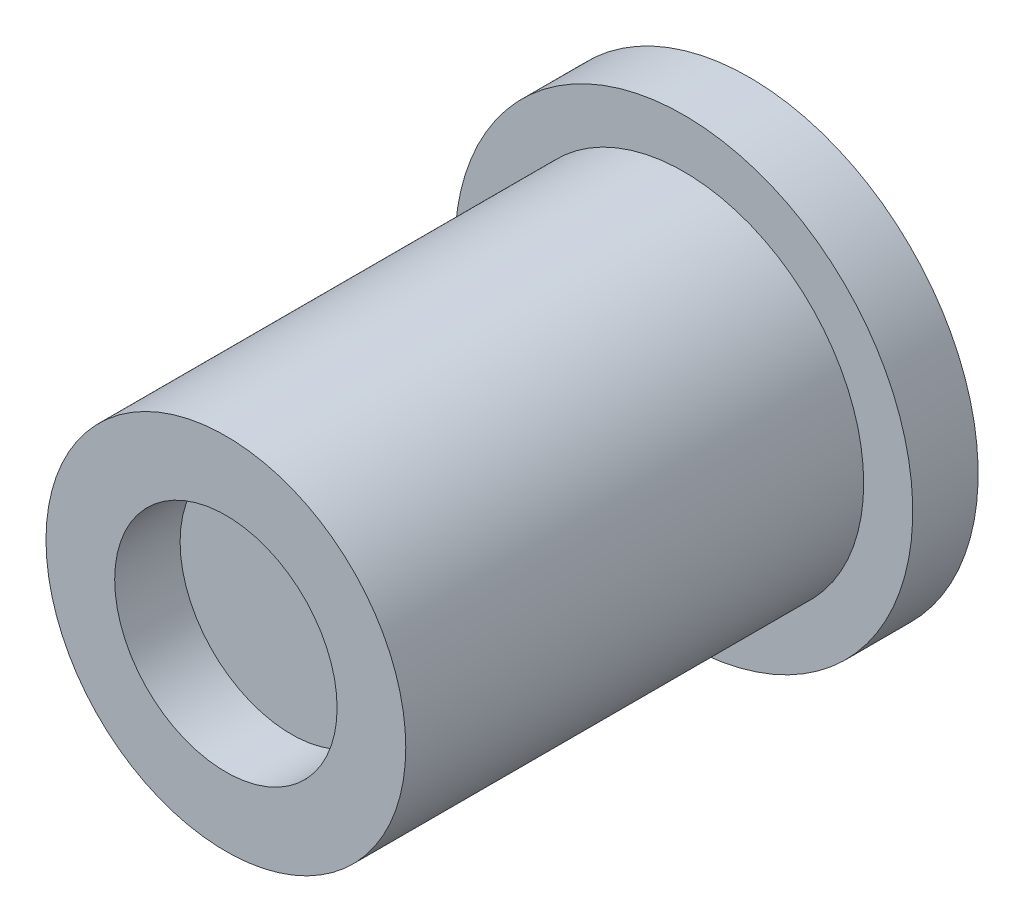
SolidWorks part; units mm, degrees
ref_plane "Спереди" through (0, 0, 0) normal (0, 0, 1) x (1, 0, 0)
ref_plane "Сверху" through (0, 0, 0) normal (0, 1, 0) x (1, 0, 0)
ref_plane "Справа" through (0, 0, 0) normal (1, 0, 0) x (0, 0, -1)
sketch "Sketch1" plane through (0, 0, 0) normal (0, 0, 1) x (1, 0, 0)
  circle A0 centre (0, 0) radius 5.5
  circle A1 centre (0, 0) radius 3.4
  dimension "D1" = 6.8
  dimension "D2" = 11
extrude "Extrude1" add sketch "Sketch1" along normal blind 2
sketch "Sketch2" plane through (0, 0, 0) normal (0, 0, -1) x (-1, 0, 0)
  circle A1 centre (0, 0) radius 5.5
  circle A2 centre (0, 0) radius 5.5
  dimension "D1" = 0
extrude "Extrude2" add sketch "Sketch2" along normal blind 12
sketch "Sketch3" plane through (0, 0, -12) normal (0, 0, -1) x (-1, 0, 0)
  circle A2 centre (0, 0) radius 7
  circle A3 centre (0, 0) radius 7
  dimension "D1" = 1.5
extrude "Extrude3" add sketch "Sketch3" along normal blind 2
